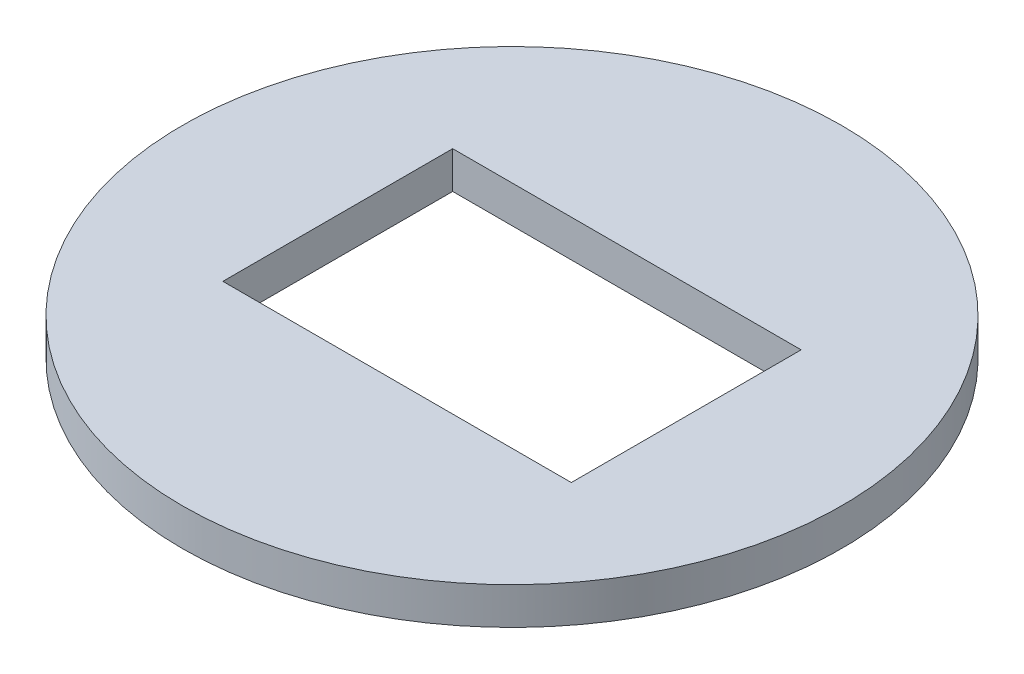
SolidWorks part; units mm, degrees
ref_plane "Front Plane" through (0, 0, 0) normal (0, 0, 1) x (1, 0, 0)
ref_plane "Top Plane" through (0, 0, 0) normal (0, 1, 0) x (1, 0, 0)
ref_plane "Right Plane" through (0, 0, 0) normal (1, 0, 0) x (0, 0, -1)
sketch "Sketch1" plane through (0, 0, 0) normal (0, 1, 0) x (1, 0, 0)
  circle A0 centre (0, 0) radius 88.9
  dimension "D1" = 177.8
extrude "Boss-Extrude1" add sketch "Sketch1" along normal blind 10
extrude "Cut-Extrude1" cut sketch "Sketch2" against normal blind 30
sketch "Sketch2" plane through (0, 0, 0) normal (0, -1, 0) x (1, 0, 0)
  line L1 (-47, 31) -> (47, 31)
  line L2 (-47, 31) -> (-47, -31)
  line L3 (-47, -31) -> (47, -31)
  line L4 (47, 31) -> (47, -31)
  line L5 (-47, 31) -> (47, -31) construction
  line L6 (-47, -31) -> (47, 31) construction
  point P0 (0, 0)
